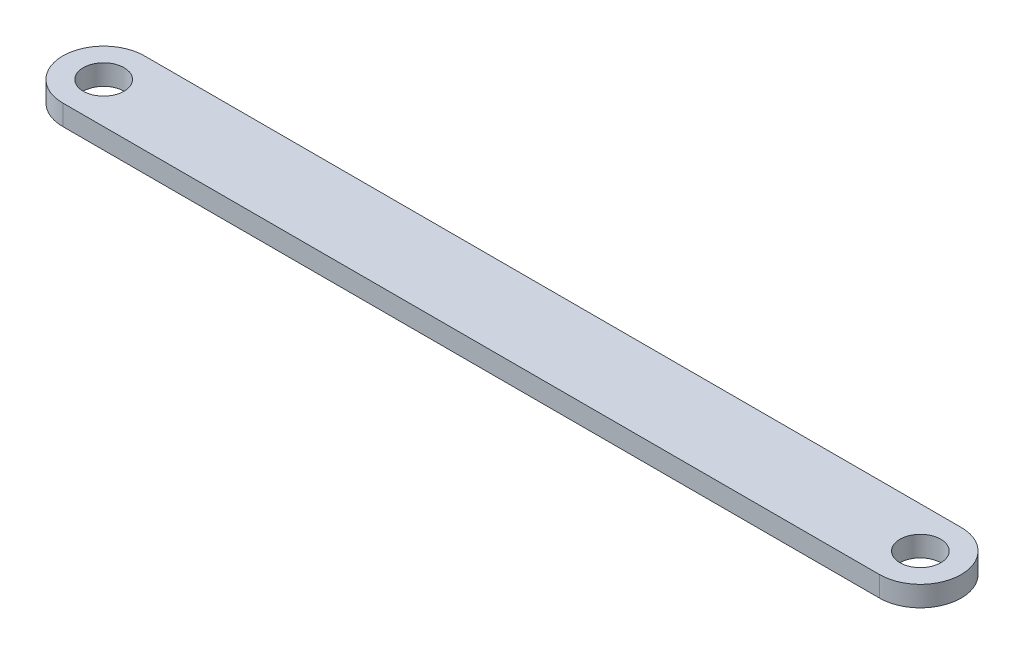
SolidWorks part; units mm, degrees
ref_plane "Ön Düzlem" through (0, 0, 0) normal (0, 0, 1) x (1, 0, 0)
ref_plane "Üst Düzlem" through (0, 0, 0) normal (0, 1, 0) x (1, 0, 0)
ref_plane "Sağ Düzlem" through (0, 0, 0) normal (1, 0, 0) x (0, 0, -1)
sketch "Sketch1" plane through (0, 0, 0) normal (0, 1, 0) x (1, 0, 0)
  line L0 (-100, 0) -> (100, 0) construction
  line L1 (-100, 10) -> (100, 10)
  line L2 (-100, -10) -> (100, -10)
  arc A0 (-100, 10) -> (-100, -10) centre (-100, 0) ccw
  arc A1 (100, -10) -> (100, 10) centre (100, 0) ccw
  circle A2 centre (-100, 0) radius 5
  circle A3 centre (100, 0) radius 5
  point P2 (0, 0)
  dimension "D1" = 10
  dimension "D3" = 10
  dimension "D4" = 10
  dimension "D2" = 200
extrude "Boss-Extrude1" add sketch "Sketch1" along normal blind 5
